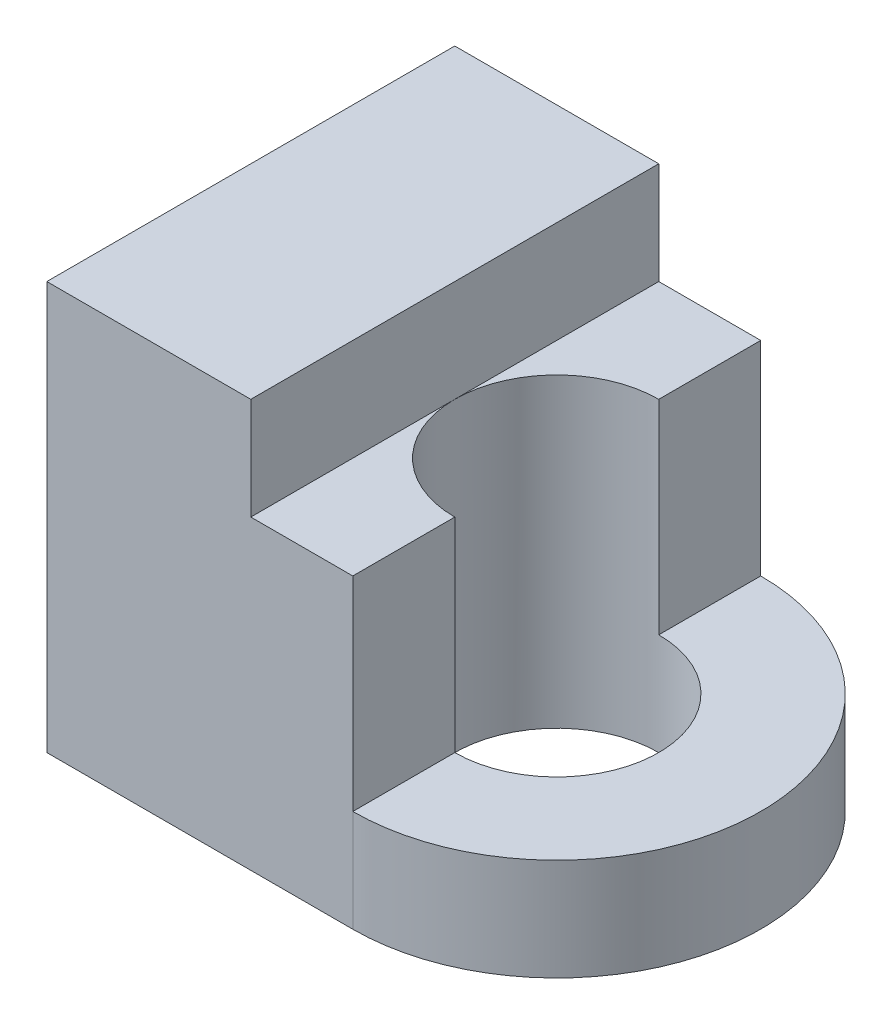
SolidWorks part; units mm, degrees
ref_plane "Front Plane" through (0, 0, 0) normal (0, 0, 1) x (1, 0, 0)
ref_plane "Top Plane" through (0, 0, 0) normal (0, 1, 0) x (1, 0, 0)
ref_plane "Right Plane" through (0, 0, 0) normal (1, 0, 0) x (0, 0, -1)
sketch "Sketch1" plane through (0, 0, 0) normal (0, 1, 0) x (1, 0, 0)
  line L0 (0, 20) -> (-30, 20)
  line L1 (-30, 20) -> (-30, -20)
  line L2 (-30, -20) -> (0, -20)
  circle A0 centre (0, 0) radius 10
  arc A1 (0, -20) -> (0, 20) centre (0, 0) ccw
  dimension "D1" = 20
  dimension "D2" = 40
  dimension "D3" = 30
extrude "Boss-Extrude1" add sketch "Sketch1" along normal blind 40
sketch "Sketch2" plane through (0, 40, 0) normal (0, 1, 0) x (1, 0, 0)
  line L0 (-30, -20) -> (0, -20) construction
  line L1 (-30, 20) -> (-10, 20)
  line L2 (-30, 20) -> (-30, -20)
  line L3 (-30, -20) -> (-10, -20)
  line L4 (-10, 20) -> (-10, -20)
  dimension "D1" = 20
extrude "Cut-Extrude1" cut sketch "Sketch2" against normal blind 10 flip side to cut
sketch "Sketch3" plane through (0, 30, 0) normal (0, 1, 0) x (1, 0, 0)
  line L1 (0, -20) -> (22.6432, -20)
  line L2 (0, -20) -> (0, 20)
  line L3 (0, 20) -> (22.6432, 20)
  line L4 (22.6432, -20) -> (22.6432, 20)
  line L6 (0, 20) -> (-10, 20) construction
extrude "Cut-Extrude2" cut sketch "Sketch3" against normal blind 20 contours L3 L4 L1 L2
